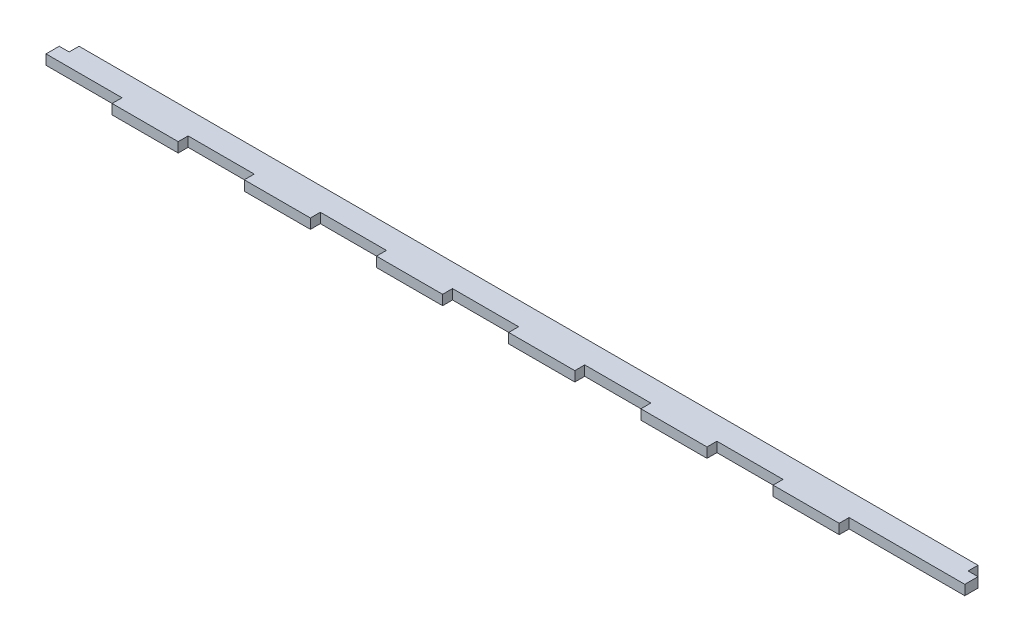
SolidWorks part; units mm, degrees
material "Balsa"
ref_plane "Alzado" through (0, 0, 0) normal (0, 0, 1) x (1, 0, 0)
ref_plane "Planta" through (0, 0, 0) normal (0, 1, 0) x (1, 0, 0)
ref_plane "Vista lateral" through (0, 0, 0) normal (1, 0, 0) x (0, 0, -1)
sketch "Croquis1" plane through (0, 0, 0) normal (0, 1, 0) x (1, 0, 0)
  line L1 (0, 0) -> (544, 0)
  line L2 (0, 0) -> (0, 20)
  line L3 (0, 20) -> (544, 20)
  line L4 (544, 0) -> (544, 20)
  dimension "D1" = 544
  dimension "D2" = 20
extrude "Saliente-Extruir1" add sketch "Croquis1" along normal blind 6
sketch "Croquis3" plane through (0, 0, 0) normal (0, 1, 0) x (1, 0, 0)
  line L0 (0, 0) -> (544, 0) construction
  line L1 (0, 0) -> (40, 0)
  line L2 (0, 0) -> (0, 6)
  line L3 (0, 6) -> (40, 6)
  line L4 (40, 0) -> (40, 6)
  line L6 (0, 20) -> (0, 0) construction
  point P8 (0, 3)
  dimension "D2" = 40
  dimension "D3" = 6
extrude "Cortar-Extruir1" cut sketch "Croquis3" along normal blind 6
pattern_linear "MatrizL1" count 7 spacing 80 along (1, 0, 0) of "Cortar-Extruir1"
sketch "Croquis4" plane through (0, 6, 0) normal (0, 1, 0) x (1, 0, 0)
  line L1 (520, 6) -> (544, 6)
  line L2 (520, 6) -> (520, 0)
  line L3 (520, 0) -> (544, 0)
  line L4 (544, 6) -> (544, 0)
extrude "Cortar-Extruir2" cut sketch "Croquis4" against normal blind 6
sketch "Croquis5" plane through (0, 0, 0) normal (0, 1, 0) x (1, 0, 0)
  line L0 (40, 6) -> (0, 6) construction
  line L1 (0, 14) -> (-6, 14)
  line L2 (0, 14) -> (0, 6)
  line L3 (0, 6) -> (-6, 6)
  line L4 (-6, 14) -> (-6, 6)
  line L5 (0, 20) -> (0, 6) construction
  line L7 (544, 6) -> (550, 6)
  line L8 (544, 6) -> (544, 14)
  line L9 (544, 14) -> (550, 14)
  line L10 (550, 6) -> (550, 14)
  dimension "D1" = 8
  dimension "D2" = 6
  dimension "D3" = 6
  dimension "D4" = 8
extrude "Saliente-Extruir3" add sketch "Croquis5" along normal blind 6
